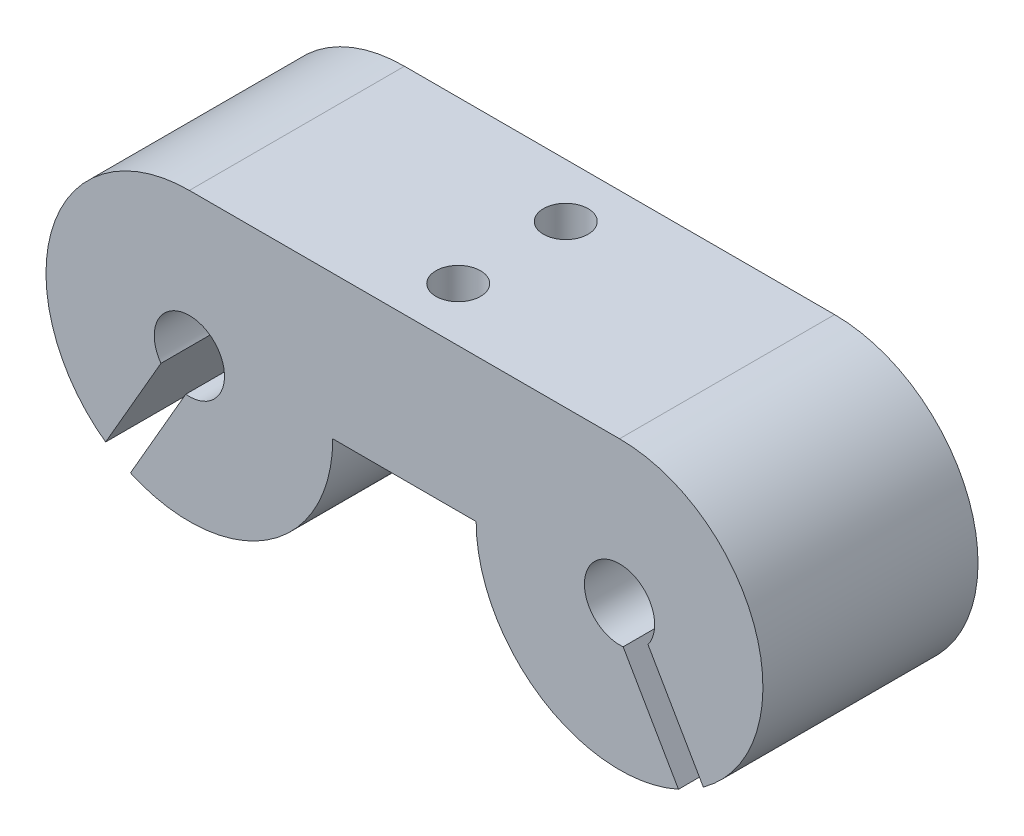
SolidWorks part; units mm, degrees
ref_plane "Front Plane" through (0, 0, 0) normal (0, 0, 1) x (1, 0, 0)
ref_plane "Top Plane" through (0, 0, 0) normal (0, 1, 0) x (1, 0, 0)
ref_plane "Right Plane" through (0, 0, 0) normal (1, 0, 0) x (0, 0, -1)
sketch "Sketch2" plane through (0, 0, 0) normal (0, 0, 1) x (1, 0, 0)
  line L0 (-15, 0) -> (15, 0) construction
  line L1 (-5, 10) -> (-15, 10)
  line L2 (-5, 10) -> (5, 10)
  line L3 (5, 10) -> (15, 10)
  line L4 (-5, 0) -> (5, 0)
  line L5 (-5, 10) -> (-5, 0) construction
  line L6 (5, 0) -> (5, 10) construction
  arc A0 (-15, 10) -> (-5, 0) centre (-15, 0) ccw
  arc A1 (5, 0) -> (15, 10) centre (15, 0) ccw
  arc A2 (-15, 10) -> (-5, 0) centre (-15, 0) cw construction
  arc A3 (15, 10) -> (5, 0) centre (15, 0) ccw construction
  dimension "D1" = 20
  dimension "D2" = 30
  dimension "D3" = 10
extrude "Boss-Extrude1" add sketch "Sketch2" along normal blind 15
sketch "Sketch3" plane through (0, 0, 15) normal (0, 0, 1) x (1, 0, 0)
  circle A0 centre (-15, 0) radius 2.45
  circle A1 centre (15, 0) radius 2.45
  dimension "D1" = 4.9
extrude "Cut-Extrude1" cut sketch "Sketch3" against normal through all
sketch "Sketch4" plane through (0, 0, 15) normal (0, 0, 1) x (1, 0, 0)
  line L0 (-14.134, -0.5) -> (-15.866, 0.5)
  line L1 (-14.134, -0.5) -> (-19.134, -9.1603)
  line L2 (-15.866, 0.5) -> (-20.866, -8.1603)
  line L3 (-19.134, -9.1603) -> (-20.866, -8.1603)
  line L4 (-5, 0) -> (5, 0) construction
  line L5 (14.134, -0.5) -> (15.866, 0.5)
  line L6 (14.134, -0.5) -> (19.134, -9.1603)
  line L7 (15.866, 0.5) -> (20.866, -8.1603)
  line L8 (19.134, -9.1603) -> (20.866, -8.1603)
  arc A0 (-15, 10) -> (-5, 0) centre (-15, 0) ccw construction
  arc A1 (5, 0) -> (15, 10) centre (15, 0) ccw construction
  point P0 (-15, 0)
  point P3 (15, 0)
  dimension "D1" = 2
  dimension "D2" = 120
  dimension "D3" = 120
extrude "Cut-Extrude2" cut sketch "Sketch4" against normal through all
hole_wizard "Ø3.0mm Clearance Dowel Hole1" positions "Sketch6" profile "Sketch5" hole size "Ø3.0" standard "DIN" end condition through all
sketch "Sketch6" plane through (0, 0, 0) normal (0, -1, 0) x (-1, 0, 0)
  line L0 (5, -7.5) -> (-5, -7.5) construction
  line L1 (5, -15) -> (5, 0) construction
  line L2 (-5, -15) -> (-5, 0) construction
  line L4 (0, -7.5) -> (0, -15) construction
  line L5 (5, -15) -> (-5, -15) construction
  line L7 (0, -7.5) -> (0, 0) construction
  point P21 (0, -3.75)
  point P23 (0, -11.25)
sketch "Sketch5" plane through (0, 0, 3.75) normal (1, 0, 0) x (0, 0, -1)
  line L0 (0, 0) -> (0, 10)
  line L1 (0, 10) -> (1.554, 10)
  line L2 (1.554, 10) -> (1.554, 0)
  line L5 (1.554, 0) -> (0, 0)
  line L11 (0, -6.35) -> (0, 107.95) construction
  dimension "Thru Hole Dia." = 3.108
  dimension "Thru Hole Depth" = 10
